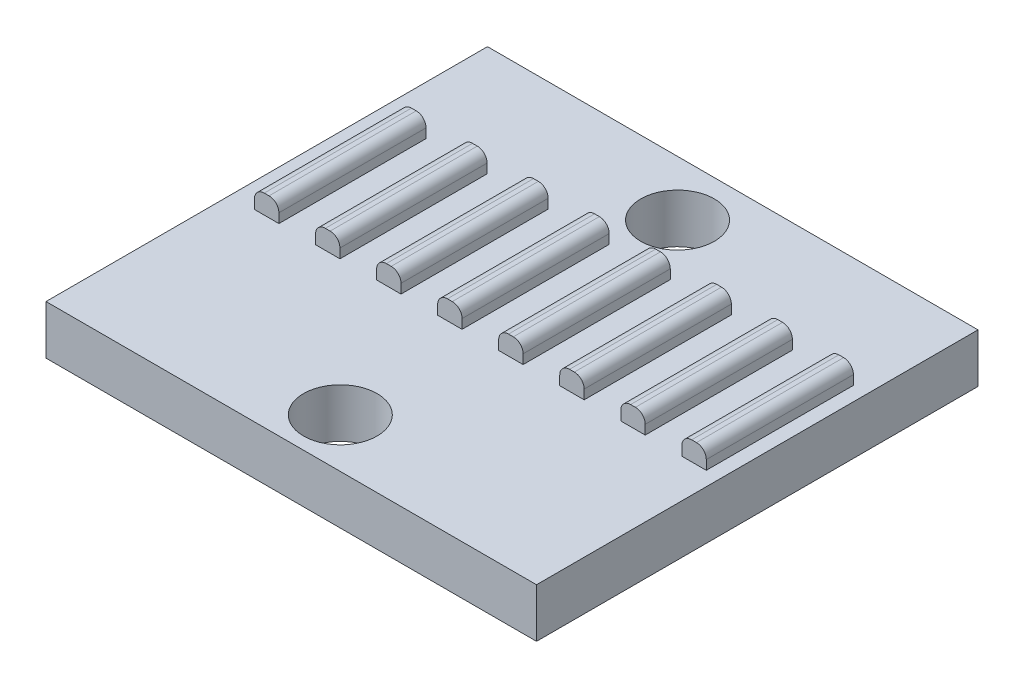
SolidWorks part; units mm, degrees
ref_plane "前视基准面" through (0, 0, 0) normal (0, 0, 1) x (1, 0, 0)
ref_plane "上视基准面" through (0, 0, 0) normal (0, 1, 0) x (1, 0, 0)
ref_plane "右视基准面" through (0, 0, 0) normal (1, 0, 0) x (0, 0, -1)
other "Configuration Table"
sketch "草图1" plane through (0, 0, 0) normal (0, 1, 0) x (1, 0, 0)
  line L1 (-10, 9) -> (10, 9)
  line L2 (-10, 9) -> (-10, -9)
  line L3 (-10, -9) -> (10, -9)
  line L4 (10, 9) -> (10, -9)
  line L5 (-10, 9) -> (10, -9) construction
  line L6 (-10, -9) -> (10, 9) construction
  point P0 (0, 0)
  dimension "D1" = 18
  dimension "D2" = 20
extrude "凸台-拉伸1" add sketch "草图1" along normal blind 2
extrude "切除-拉伸1" cut sketch "草图2" against normal blind 2
sketch "草图2" plane through (-240.6478, 2, 128.9977) normal (0, 1, 0) x (-0.0379, 0, 0.9993)
  circle A2 centre (-131.0286, 235.8523) radius 1.45
  circle A3 centre (-144.7687, 235.3313) radius 1.45
sketch "草图6" plane through (0, 2, 0) normal (0, 1, 0) x (1, 0, 0)
  line L32 (9.4213, 4.5) -> (8.4255, 4.5)
  line L33 (8.4255, 4.5) -> (8.4255, -1.5)
  line L34 (8.4255, -1.5) -> (9.4213, -1.5)
  line L35 (9.4213, -1.5) -> (9.4213, 4.5)
  line L36 (6.9319, 4.5) -> (5.9362, 4.5)
  line L37 (5.9362, 4.5) -> (5.9362, -1.5)
  line L38 (5.9362, -1.5) -> (6.9319, -1.5)
  line L39 (6.9319, -1.5) -> (6.9319, 4.5)
  line L40 (4.4426, 4.5) -> (3.4468, 4.5)
  line L41 (3.4468, 4.5) -> (3.4468, -1.5)
  line L42 (3.4468, -1.5) -> (4.4426, -1.5)
  line L43 (4.4426, -1.5) -> (4.4426, 4.5)
  line L44 (1.9532, 4.5) -> (0.9574, 4.5)
  line L45 (0.9574, 4.5) -> (0.9574, -1.5)
  line L46 (0.9574, -1.5) -> (1.9532, -1.5)
  line L47 (1.9532, -1.5) -> (1.9532, 4.5)
  line L48 (-0.5362, 4.5) -> (-1.5319, 4.5)
  line L49 (-1.5319, 4.5) -> (-1.5319, -1.5)
  line L50 (-1.5319, -1.5) -> (-0.5362, -1.5)
  line L51 (-0.5362, -1.5) -> (-0.5362, 4.5)
  line L52 (-3.0255, 4.5) -> (-4.0213, 4.5)
  line L53 (-4.0213, 4.5) -> (-4.0213, -1.5)
  line L54 (-4.0213, -1.5) -> (-3.0255, -1.5)
  line L55 (-3.0255, -1.5) -> (-3.0255, 4.5)
  line L56 (-5.5149, 4.5) -> (-6.5106, 4.5)
  line L57 (-6.5106, 4.5) -> (-6.5106, -1.5)
  line L58 (-6.5106, -1.5) -> (-5.5149, -1.5)
  line L59 (-5.5149, -1.5) -> (-5.5149, 4.5)
  line L60 (-9, 4.5) -> (-9, -1.5)
  line L61 (-9, -1.5) -> (-8.0043, -1.5)
  line L62 (-8.0043, -1.5) -> (-8.0043, 4.5)
  line L63 (-8.0043, 4.5) -> (-9, 4.5)
extrude "凸台-拉伸4" add sketch "草图6" along normal blind 0.78 separate body
fillet "圆角11" radius 0.4 2 edges at (-8.0043, 2.78, -1.5) (-9, 2.78, -1.5)
fillet "圆角12" radius 0.4 2 edges at (-5.5149, 2.78, -1.5) (-6.5106, 2.78, -1.5)
fillet "圆角13" radius 0.4 2 edges at (-3.0255, 2.78, -1.5) (-4.0213, 2.78, -1.5)
fillet "圆角14" radius 0.4 1 edges at (-1.5319, 2.78, -1.5)
fillet "圆角15" radius 0.4 1 edges at (-0.5362, 2.78, -1.5)
fillet "圆角16" radius 0.4 2 edges at (1.9532, 2.78, -1.5) (0.9574, 2.78, -1.5)
fillet "圆角17" radius 0.4 2 edges at (4.4426, 2.78, -1.5) (3.4468, 2.78, -1.5)
fillet "圆角18" radius 0.4 2 edges at (6.9319, 2.78, -1.5) (5.9362, 2.78, -1.5)
fillet "圆角19" radius 0.4 2 edges at (9.4213, 2.78, -1.5) (8.4255, 2.78, -1.5)
sketch "草图9" plane through (0, 2, 0) normal (0, 1, 0) x (1, 0, 0)
  line L0 (0, -9) -> (0, -7) construction
  line L1 (-10, -9) -> (10, -9) construction
  line L2 (0, 9) -> (0, 6.75) construction
  line L3 (10, 9) -> (-10, 9) construction
  circle A0 centre (0, -7) radius 1.5
  circle A1 centre (0, 6.75) radius 1.5
  dimension "D2" = 3
  dimension "D4" = 3
  dimension "D1" = 2
  dimension "D3" = 2.25
extrude "切除-拉伸2" cut sketch "草图9" against normal blind 10
